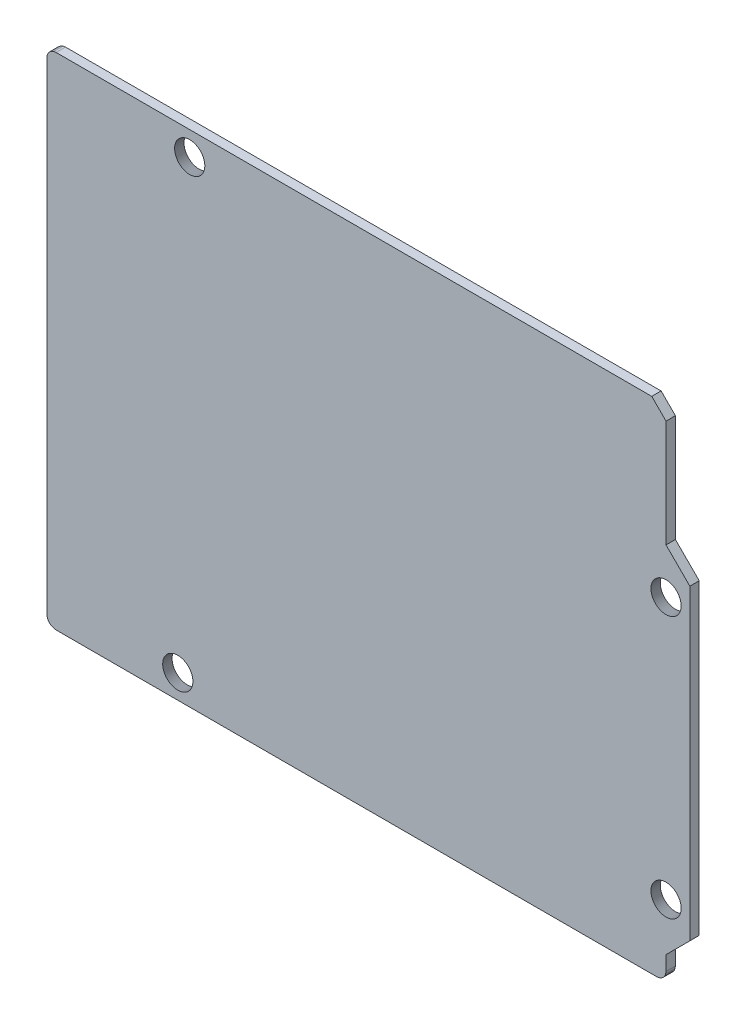
SolidWorks part; units mm, degrees
material "ПТФЭ (общий)"
ref_plane "Спереди" through (0, 0, 0) normal (0, 0, 1) x (1, 0, 0)
ref_plane "Сверху" through (0, 0, 0) normal (0, 1, 0) x (1, 0, 0)
ref_plane "Справа" through (0, 0, 0) normal (1, 0, 0) x (0, 0, -1)
sketch "Model" plane through (0, 0, 0) normal (0, 0, 1) x (1, 0, 0)
  line L0 (15.2346, 207.8414) -> (15.2907, 207.8424)
  line L1 (15.2907, 207.8424) -> (15.3468, 207.8453)
  line L2 (15.3468, 207.8453) -> (15.4027, 207.8502)
  line L3 (15.4027, 207.8502) -> (15.4584, 207.8571)
  line L4 (15.4584, 207.8571) -> (15.5139, 207.8658)
  line L5 (15.5139, 207.8658) -> (15.569, 207.8766)
  line L6 (15.569, 207.8766) -> (15.6237, 207.8892)
  line L7 (15.6237, 207.8892) -> (15.6779, 207.9037)
  line L8 (15.6779, 207.9037) -> (15.7315, 207.9201)
  line L9 (15.7315, 207.9201) -> (15.7846, 207.9384)
  line L10 (15.7846, 207.9384) -> (15.837, 207.9585)
  line L11 (15.837, 207.9585) -> (15.8887, 207.9804)
  line L12 (15.8887, 207.9804) -> (15.9396, 208.0042)
  line L13 (15.9396, 208.0042) -> (15.9896, 208.0296)
  line L14 (15.9896, 208.0296) -> (16.0387, 208.0569)
  line L15 (16.0387, 208.0569) -> (16.0868, 208.0858)
  line L16 (16.0868, 208.0858) -> (16.1339, 208.1163)
  line L17 (16.1339, 208.1163) -> (16.1798, 208.1485)
  line L18 (16.1798, 208.1485) -> (16.2247, 208.1823)
  line L19 (16.2247, 208.1823) -> (16.2683, 208.2176)
  line L20 (16.2683, 208.2176) -> (16.3106, 208.2545)
  line L21 (16.3106, 208.2545) -> (16.3517, 208.2927)
  line L22 (16.3517, 208.2927) -> (16.3914, 208.3324)
  line L23 (16.3914, 208.3324) -> (16.4297, 208.3735)
  line L24 (16.4297, 208.3735) -> (16.4665, 208.4158)
  line L25 (16.4665, 208.4158) -> (16.5018, 208.4595)
  line L26 (16.5018, 208.4595) -> (16.5356, 208.5043)
  line L27 (16.5356, 208.5043) -> (16.5678, 208.5503)
  line L28 (16.5678, 208.5503) -> (16.5984, 208.5974)
  line L29 (16.5984, 208.5974) -> (16.6273, 208.6455)
  line L30 (16.6273, 208.6455) -> (16.6545, 208.6946)
  line L31 (16.6545, 208.6946) -> (16.68, 208.7446)
  line L32 (16.68, 208.7446) -> (16.7037, 208.7954)
  line L33 (16.7037, 208.7954) -> (16.7256, 208.8471)
  line L34 (16.7256, 208.8471) -> (16.7457, 208.8995)
  line L35 (16.7457, 208.8995) -> (16.764, 208.9526)
  line L36 (16.764, 208.9526) -> (16.7804, 209.0063)
  line L37 (16.7804, 209.0063) -> (16.7949, 209.0605)
  line L38 (16.7949, 209.0605) -> (16.8076, 209.1152)
  line L39 (16.8076, 209.1152) -> (16.8183, 209.1703)
  line L40 (16.8183, 209.1703) -> (16.8271, 209.2257)
  line L41 (16.8271, 209.2257) -> (16.8339, 209.2814)
  line L42 (16.8339, 209.2814) -> (16.8388, 209.3373)
  line L43 (16.8388, 209.3373) -> (16.8417, 209.3934)
  line L44 (16.8417, 209.3934) -> (16.8427, 209.4495)
  line L45 (16.8427, 209.4495) -> (16.8418, 209.5052)
  line L46 (16.8418, 209.5052) -> (16.8389, 209.5609)
  line L47 (16.8389, 209.5609) -> (16.834, 209.6164)
  line L48 (16.834, 209.6164) -> (16.8273, 209.6717)
  line L49 (16.8273, 209.6717) -> (16.8186, 209.7267)
  line L50 (16.8186, 209.7267) -> (16.8081, 209.7814)
  line L51 (16.8081, 209.7814) -> (16.7956, 209.8357)
  line L52 (16.7956, 209.8357) -> (16.7813, 209.8896)
  line L53 (16.7813, 209.8896) -> (16.7652, 209.9429)
  line L54 (16.7652, 209.9429) -> (16.7471, 209.9956)
  line L55 (16.7471, 209.9956) -> (16.7273, 210.0477)
  line L56 (16.7273, 210.0477) -> (16.7057, 210.0991)
  line L57 (16.7057, 210.0991) -> (16.6823, 210.1496)
  line L58 (16.6823, 210.1496) -> (16.6572, 210.1994)
  line L59 (16.6572, 210.1994) -> (16.6304, 210.2482)
  line L60 (16.6304, 210.2482) -> (16.6018, 210.2961)
  line L61 (16.6018, 210.2961) -> (16.5717, 210.3429)
  line L62 (16.5717, 210.3429) -> (16.5399, 210.3887)
  line L63 (16.5399, 210.3887) -> (16.5066, 210.4334)
  line L64 (16.5066, 210.4334) -> (16.4718, 210.4768)
  line L65 (16.4718, 210.4768) -> (16.4354, 210.5191)
  line L66 (16.4354, 210.5191) -> (16.3977, 210.56)
  line L67 (16.3977, 210.56) -> (16.3585, 210.5997)
  line L68 (16.3585, 210.5997) -> (16.318, 210.6379)
  line L69 (16.318, 210.6379) -> (16.2762, 210.6747)
  line L70 (16.2762, 210.6747) -> (16.2331, 210.7101)
  line L71 (16.2331, 210.7101) -> (16.1888, 210.7439)
  line L72 (16.1888, 210.7439) -> (16.1434, 210.7762)
  line L73 (16.1434, 210.7762) -> (16.0969, 210.8069)
  line L74 (16.0969, 210.8069) -> (16.0494, 210.8359)
  line L75 (16.0494, 210.8359) -> (16.0008, 210.8633)
  line L76 (16.0008, 210.8633) -> (15.9514, 210.889)
  line L77 (15.9514, 210.889) -> (15.9011, 210.913)
  line L78 (15.9011, 210.913) -> (15.85, 210.9352)
  line L79 (15.85, 210.9352) -> (15.7982, 210.9556)
  line L80 (15.7982, 210.9556) -> (15.7457, 210.9742)
  line L81 (15.7457, 210.9742) -> (15.6925, 210.991)
  line L82 (15.6925, 210.991) -> (15.6389, 211.006)
  line L83 (15.6389, 211.006) -> (15.5847, 211.019)
  line L84 (15.5847, 211.019) -> (15.5301, 211.0302)
  line L85 (15.5301, 211.0302) -> (15.4752, 211.0395)
  line L86 (15.4752, 211.0395) -> (15.4199, 211.0469)
  line L87 (15.4199, 211.0469) -> (15.3645, 211.0524)
  line L88 (15.3645, 211.0524) -> (15.3089, 211.0559)
  line L89 (15.3089, 211.0559) -> (15.2532, 211.0575)
  line L90 (15.2532, 211.0575) -> (15.1975, 211.0572)
  line L91 (15.1975, 211.0572) -> (15.1418, 211.0549)
  line L92 (15.1418, 211.0549) -> (15.0862, 211.0508)
  line L93 (15.0862, 211.0508) -> (15.0309, 211.0447)
  line L94 (15.0309, 211.0447) -> (14.9757, 211.0366)
  line L95 (14.9757, 211.0366) -> (14.9209, 211.0267)
  line L96 (14.9209, 211.0267) -> (14.8664, 211.0149)
  line L97 (14.8664, 211.0149) -> (14.8124, 211.0012)
  line L98 (14.8124, 211.0012) -> (14.7589, 210.9856)
  line L99 (14.7589, 210.9856) -> (14.706, 210.9682)
  line L100 (14.706, 210.9682) -> (14.6537, 210.949)
  line L101 (14.6537, 210.949) -> (14.6021, 210.928)
  line L102 (14.6021, 210.928) -> (14.5513, 210.9052)
  line L103 (14.5513, 210.9052) -> (14.5012, 210.8806)
  line L104 (14.5012, 210.8806) -> (14.4521, 210.8544)
  line L105 (14.4521, 210.8544) -> (14.4039, 210.8264)
  line L106 (14.4039, 210.8264) -> (14.3567, 210.7968)
  line L107 (14.3567, 210.7968) -> (14.3106, 210.7656)
  line L108 (14.3106, 210.7656) -> (14.2655, 210.7328)
  line L109 (14.2655, 210.7328) -> (14.2216, 210.6985)
  line L110 (14.2216, 210.6985) -> (14.179, 210.6626)
  line L111 (14.179, 210.6626) -> (14.1376, 210.6253)
  line L112 (14.1376, 210.6253) -> (14.0975, 210.5866)
  line L113 (14.0975, 210.5866) -> (14.0588, 210.5465)
  line L114 (14.0588, 210.5465) -> (14.0215, 210.5051)
  line L115 (14.0215, 210.5051) -> (13.9857, 210.4625)
  line L116 (13.9857, 210.4625) -> (13.9513, 210.4186)
  line L117 (13.9513, 210.4186) -> (13.9185, 210.3736)
  line L118 (13.9185, 210.3736) -> (13.8873, 210.3274)
  line L119 (13.8873, 210.3274) -> (13.8577, 210.2802)
  line L120 (13.8577, 210.2802) -> (13.8297, 210.232)
  line L121 (13.8297, 210.232) -> (13.8035, 210.1829)
  line L122 (13.8035, 210.1829) -> (13.7789, 210.1329)
  line L123 (13.7789, 210.1329) -> (13.7561, 210.082)
  line L124 (13.7561, 210.082) -> (13.7351, 210.0304)
  line L125 (13.7351, 210.0304) -> (13.7159, 209.9781)
  line L126 (13.7159, 209.9781) -> (13.6985, 209.9252)
  line L127 (13.6985, 209.9252) -> (13.6829, 209.8717)
  line L128 (13.6829, 209.8717) -> (13.6692, 209.8177)
  line L129 (13.6692, 209.8177) -> (13.6574, 209.7632)
  line L130 (13.6574, 209.7632) -> (13.6475, 209.7084)
  line L131 (13.6475, 209.7084) -> (13.6395, 209.6533)
  line L132 (13.6395, 209.6533) -> (13.6334, 209.5979)
  line L133 (13.6334, 209.5979) -> (13.6292, 209.5423)
  line L134 (13.6292, 209.5423) -> (13.6269, 209.4867)
  line L135 (13.6269, 209.4867) -> (13.6266, 209.4309)
  line L136 (13.6266, 209.4309) -> (13.6282, 209.3752)
  line L137 (13.6282, 209.3752) -> (13.6318, 209.3196)
  line L138 (13.6318, 209.3196) -> (13.6372, 209.2642)
  line L139 (13.6372, 209.2642) -> (13.6446, 209.209)
  line L140 (13.6446, 209.209) -> (13.6539, 209.154)
  line L141 (13.6539, 209.154) -> (13.6651, 209.0994)
  line L142 (13.6651, 209.0994) -> (13.6782, 209.0453)
  line L143 (13.6782, 209.0453) -> (13.6931, 208.9916)
  line L144 (13.6931, 208.9916) -> (13.7099, 208.9385)
  line L145 (13.7099, 208.9385) -> (13.7285, 208.886)
  line L146 (13.7285, 208.886) -> (13.7489, 208.8341)
  line L147 (13.7489, 208.8341) -> (13.7711, 208.783)
  line L148 (13.7711, 208.783) -> (13.7951, 208.7327)
  line L149 (13.7951, 208.7327) -> (13.8208, 208.6833)
  line L150 (13.8208, 208.6833) -> (13.8482, 208.6348)
  line L151 (13.8482, 208.6348) -> (13.8773, 208.5872)
  line L152 (13.8773, 208.5872) -> (13.9079, 208.5407)
  line L153 (13.9079, 208.5407) -> (13.9402, 208.4953)
  line L154 (13.9402, 208.4953) -> (13.9741, 208.451)
  line L155 (13.9741, 208.451) -> (14.0094, 208.408)
  line L156 (14.0094, 208.408) -> (14.0462, 208.3661)
  line L157 (14.0462, 208.3661) -> (14.0845, 208.3256)
  line L158 (14.0845, 208.3256) -> (14.1241, 208.2865)
  line L159 (14.1241, 208.2865) -> (14.165, 208.2487)
  line L160 (14.165, 208.2487) -> (14.2073, 208.2123)
  line L161 (14.2073, 208.2123) -> (14.2508, 208.1775)
  line L162 (14.2508, 208.1775) -> (14.2954, 208.1442)
  line L163 (14.2954, 208.1442) -> (14.3412, 208.1124)
  line L164 (14.3412, 208.1124) -> (14.3881, 208.0823)
  line L165 (14.3881, 208.0823) -> (14.4359, 208.0538)
  line L166 (14.4359, 208.0538) -> (14.4848, 208.0269)
  line L167 (14.4848, 208.0269) -> (14.5345, 208.0018)
  line L168 (14.5345, 208.0018) -> (14.5851, 207.9784)
  line L169 (14.5851, 207.9784) -> (14.6364, 207.9568)
  line L170 (14.6364, 207.9568) -> (14.6885, 207.937)
  line L171 (14.6885, 207.937) -> (14.7412, 207.919)
  line L172 (14.7412, 207.919) -> (14.7945, 207.9028)
  line L173 (14.7945, 207.9028) -> (14.8484, 207.8885)
  line L174 (14.8484, 207.8885) -> (14.9027, 207.876)
  line L175 (14.9027, 207.876) -> (14.9574, 207.8655)
  line L176 (14.9574, 207.8655) -> (15.0124, 207.8568)
  line L177 (15.0124, 207.8568) -> (15.0678, 207.8501)
  line L178 (15.0678, 207.8501) -> (15.1233, 207.8453)
  line L179 (15.1233, 207.8453) -> (15.1789, 207.8424)
  line L180 (15.1789, 207.8424) -> (15.2346, 207.8414)
  line L1114 (0.9945, 211.9886) -> (64.4721, 211.9886)
  line L1115 (0.7406, 211.9463) -> (0.9945, 211.9886)
  line L1116 (0.5078, 211.8405) -> (0.7406, 211.9463)
  line L1117 (0.2962, 211.6924) -> (0.5078, 211.8405)
  line L1118 (0.127, 211.4808) -> (0.2962, 211.6924)
  line L1119 (0.0423, 211.248) -> (0.127, 211.4808)
  line L1120 (0, 210.973) -> (0.0423, 211.248)
  line L1121 (0, 159.6831) -> (0, 210.973)
  line L1122 (0.0423, 159.4292) -> (0, 159.6831)
  line L1123 (0.127, 159.1964) -> (0.0423, 159.4292)
  line L1124 (0.2962, 158.9848) -> (0.127, 159.1964)
  line L1125 (0.5078, 158.8156) -> (0.2962, 158.9848)
  line L1126 (0.7406, 158.7309) -> (0.5078, 158.8156)
  line L1127 (0.9945, 158.6886) -> (0.7406, 158.7309)
  line L1128 (65.001, 158.6886) -> (0.9945, 158.6886)
  line L1129 (65.2549, 158.7309) -> (65.001, 158.6886)
  line L1130 (65.4877, 158.8156) -> (65.2549, 158.7309)
  line L1131 (65.6993, 158.9848) -> (65.4877, 158.8156)
  line L1132 (65.8686, 159.1964) -> (65.6993, 158.9848)
  line L1133 (65.9532, 159.4292) -> (65.8686, 159.1964)
  line L1134 (65.9955, 159.6831) -> (65.9532, 159.4292)
  line L1135 (65.9955, 161.2277) -> (65.9955, 159.6831)
  line L1136 (68.5346, 163.7668) -> (65.9955, 161.2277)
  line L1137 (68.5346, 196.5001) -> (68.5346, 163.7668)
  line L1138 (65.9955, 199.0392) -> (68.5346, 196.5001)
  line L1139 (65.9955, 210.4652) -> (65.9955, 199.0392)
  line L1140 (64.4721, 211.9886) -> (65.9955, 210.4652)
  line L1141 (65.9955, 192.6068) -> (66.0516, 192.6078)
  line L1142 (66.0516, 192.6078) -> (66.1077, 192.6107)
  line L1143 (66.1077, 192.6107) -> (66.1636, 192.6156)
  line L1144 (66.1636, 192.6156) -> (66.2193, 192.6224)
  line L1145 (66.2193, 192.6224) -> (66.2748, 192.6312)
  line L1146 (66.2748, 192.6312) -> (66.3299, 192.6419)
  line L1147 (66.3299, 192.6419) -> (66.3845, 192.6546)
  line L1148 (66.3845, 192.6546) -> (66.4388, 192.6691)
  line L1149 (66.4388, 192.6691) -> (66.4924, 192.6855)
  line L1150 (66.4924, 192.6855) -> (66.5455, 192.7038)
  line L1151 (66.5455, 192.7038) -> (66.5979, 192.7239)
  line L1152 (66.5979, 192.7239) -> (66.6496, 192.7458)
  line L1153 (66.6496, 192.7458) -> (66.7005, 192.7695)
  line L1154 (66.7005, 192.7695) -> (66.7505, 192.795)
  line L1155 (66.7505, 192.795) -> (66.7996, 192.8222)
  line L1156 (66.7996, 192.8222) -> (66.8477, 192.8512)
  line L1157 (66.8477, 192.8512) -> (66.8948, 192.8817)
  line L1158 (66.8948, 192.8817) -> (66.9407, 192.9139)
  line L1159 (66.9407, 192.9139) -> (66.9856, 192.9477)
  line L1160 (66.9856, 192.9477) -> (67.0292, 192.983)
  line L1161 (67.0292, 192.983) -> (67.0715, 193.0198)
  line L1162 (67.0715, 193.0198) -> (67.1126, 193.0581)
  line L1163 (67.1126, 193.0581) -> (67.1523, 193.0978)
  line L1164 (67.1523, 193.0978) -> (67.1906, 193.1389)
  line L1165 (67.1906, 193.1389) -> (67.2274, 193.1812)
  line L1166 (67.2274, 193.1812) -> (67.2627, 193.2249)
  line L1167 (67.2627, 193.2249) -> (67.2965, 193.2697)
  line L1168 (67.2965, 193.2697) -> (67.3287, 193.3157)
  line L1169 (67.3287, 193.3157) -> (67.3593, 193.3627)
  line L1170 (67.3593, 193.3627) -> (67.3882, 193.4108)
  line L1171 (67.3882, 193.4108) -> (67.4154, 193.4599)
  line L1172 (67.4154, 193.4599) -> (67.4409, 193.51)
  line L1173 (67.4409, 193.51) -> (67.4646, 193.5608)
  line L1174 (67.4646, 193.5608) -> (67.4865, 193.6125)
  line L1175 (67.4865, 193.6125) -> (67.5066, 193.6649)
  line L1176 (67.5066, 193.6649) -> (67.5249, 193.718)
  line L1177 (67.5249, 193.718) -> (67.5413, 193.7716)
  line L1178 (67.5413, 193.7716) -> (67.5558, 193.8259)
  line L1179 (67.5558, 193.8259) -> (67.5685, 193.8806)
  line L1180 (67.5685, 193.8806) -> (67.5792, 193.9357)
  line L1181 (67.5792, 193.9357) -> (67.588, 193.9911)
  line L1182 (67.588, 193.9911) -> (67.5948, 194.0468)
  line L1183 (67.5948, 194.0468) -> (67.5997, 194.1027)
  line L1184 (67.5997, 194.1027) -> (67.6026, 194.1588)
  line L1185 (67.6026, 194.1588) -> (67.6036, 194.2149)
  line L1186 (67.6036, 194.2149) -> (67.6026, 194.2706)
  line L1187 (67.6026, 194.2706) -> (67.5998, 194.3262)
  line L1188 (67.5998, 194.3262) -> (67.5949, 194.3818)
  line L1189 (67.5949, 194.3818) -> (67.5882, 194.4371)
  line L1190 (67.5882, 194.4371) -> (67.5795, 194.4921)
  line L1191 (67.5795, 194.4921) -> (67.569, 194.5468)
  line L1192 (67.569, 194.5468) -> (67.5565, 194.6011)
  line L1193 (67.5565, 194.6011) -> (67.5422, 194.655)
  line L1194 (67.5422, 194.655) -> (67.5261, 194.7083)
  line L1195 (67.5261, 194.7083) -> (67.508, 194.761)
  line L1196 (67.508, 194.761) -> (67.4882, 194.8131)
  line L1197 (67.4882, 194.8131) -> (67.4666, 194.8644)
  line L1198 (67.4666, 194.8644) -> (67.4432, 194.915)
  line L1199 (67.4432, 194.915) -> (67.4181, 194.9647)
  line L1200 (67.4181, 194.9647) -> (67.3913, 195.0136)
  line L1201 (67.3913, 195.0136) -> (67.3627, 195.0615)
  line L1202 (67.3627, 195.0615) -> (67.3326, 195.1083)
  line L1203 (67.3326, 195.1083) -> (67.3008, 195.1541)
  line L1204 (67.3008, 195.1541) -> (67.2675, 195.1987)
  line L1205 (67.2675, 195.1987) -> (67.2327, 195.2422)
  line L1206 (67.2327, 195.2422) -> (67.1963, 195.2845)
  line L1207 (67.1963, 195.2845) -> (67.1586, 195.3254)
  line L1208 (67.1586, 195.3254) -> (67.1194, 195.3651)
  line L1209 (67.1194, 195.3651) -> (67.0789, 195.4033)
  line L1210 (67.0789, 195.4033) -> (67.0371, 195.4401)
  line L1211 (67.0371, 195.4401) -> (66.994, 195.4755)
  line L1212 (66.994, 195.4755) -> (66.9497, 195.5093)
  line L1213 (66.9497, 195.5093) -> (66.9043, 195.5416)
  line L1214 (66.9043, 195.5416) -> (66.8578, 195.5723)
  line L1215 (66.8578, 195.5723) -> (66.8103, 195.6013)
  line L1216 (66.8103, 195.6013) -> (66.7617, 195.6287)
  line L1217 (66.7617, 195.6287) -> (66.7123, 195.6544)
  line L1218 (66.7123, 195.6544) -> (66.662, 195.6784)
  line L1219 (66.662, 195.6784) -> (66.6109, 195.7006)
  line L1220 (66.6109, 195.7006) -> (66.5591, 195.721)
  line L1221 (66.5591, 195.721) -> (66.5066, 195.7396)
  line L1222 (66.5066, 195.7396) -> (66.4534, 195.7564)
  line L1223 (66.4534, 195.7564) -> (66.3997, 195.7714)
  line L1224 (66.3997, 195.7714) -> (66.3456, 195.7844)
  line L1225 (66.3456, 195.7844) -> (66.291, 195.7956)
  line L1226 (66.291, 195.7956) -> (66.2361, 195.8049)
  line L1227 (66.2361, 195.8049) -> (66.1808, 195.8123)
  line L1228 (66.1808, 195.8123) -> (66.1254, 195.8177)
  line L1229 (66.1254, 195.8177) -> (66.0698, 195.8213)
  line L1230 (66.0698, 195.8213) -> (66.0141, 195.8229)
  line L1231 (66.0141, 195.8229) -> (65.9584, 195.8226)
  line L1232 (65.9584, 195.8226) -> (65.9027, 195.8203)
  line L1233 (65.9027, 195.8203) -> (65.8471, 195.8161)
  line L1234 (65.8471, 195.8161) -> (65.7918, 195.81)
  line L1235 (65.7918, 195.81) -> (65.7366, 195.802)
  line L1236 (65.7366, 195.802) -> (65.6818, 195.7921)
  line L1237 (65.6818, 195.7921) -> (65.6273, 195.7803)
  line L1238 (65.6273, 195.7803) -> (65.5733, 195.7666)
  line L1239 (65.5733, 195.7666) -> (65.5198, 195.751)
  line L1240 (65.5198, 195.751) -> (65.4669, 195.7336)
  line L1241 (65.4669, 195.7336) -> (65.4146, 195.7144)
  line L1242 (65.4146, 195.7144) -> (65.363, 195.6934)
  line L1243 (65.363, 195.6934) -> (65.3122, 195.6706)
  line L1244 (65.3122, 195.6706) -> (65.2621, 195.646)
  line L1245 (65.2621, 195.646) -> (65.213, 195.6198)
  line L1246 (65.213, 195.6198) -> (65.1648, 195.5918)
  line L1247 (65.1648, 195.5918) -> (65.1176, 195.5622)
  line L1248 (65.1176, 195.5622) -> (65.0715, 195.531)
  line L1249 (65.0715, 195.531) -> (65.0264, 195.4982)
  line L1250 (65.0264, 195.4982) -> (64.9825, 195.4638)
  line L1251 (64.9825, 195.4638) -> (64.9399, 195.428)
  line L1252 (64.9399, 195.428) -> (64.8985, 195.3907)
  line L1253 (64.8985, 195.3907) -> (64.8584, 195.352)
  line L1254 (64.8584, 195.352) -> (64.8197, 195.3119)
  line L1255 (64.8197, 195.3119) -> (64.7824, 195.2705)
  line L1256 (64.7824, 195.2705) -> (64.7466, 195.2279)
  line L1257 (64.7466, 195.2279) -> (64.7122, 195.184)
  line L1258 (64.7122, 195.184) -> (64.6794, 195.139)
  line L1259 (64.6794, 195.139) -> (64.6482, 195.0928)
  line L1260 (64.6482, 195.0928) -> (64.6186, 195.0456)
  line L1261 (64.6186, 195.0456) -> (64.5906, 194.9974)
  line L1262 (64.5906, 194.9974) -> (64.5644, 194.9483)
  line L1263 (64.5644, 194.9483) -> (64.5398, 194.8982)
  line L1264 (64.5398, 194.8982) -> (64.517, 194.8474)
  line L1265 (64.517, 194.8474) -> (64.496, 194.7958)
  line L1266 (64.496, 194.7958) -> (64.4768, 194.7435)
  line L1267 (64.4768, 194.7435) -> (64.4594, 194.6906)
  line L1268 (64.4594, 194.6906) -> (64.4438, 194.6371)
  line L1269 (64.4438, 194.6371) -> (64.4301, 194.5831)
  line L1270 (64.4301, 194.5831) -> (64.4183, 194.5286)
  line L1271 (64.4183, 194.5286) -> (64.4084, 194.4738)
  line L1272 (64.4084, 194.4738) -> (64.4004, 194.4187)
  line L1273 (64.4004, 194.4187) -> (64.3943, 194.3633)
  line L1274 (64.3943, 194.3633) -> (64.3901, 194.3077)
  line L1275 (64.3901, 194.3077) -> (64.3878, 194.252)
  line L1276 (64.3878, 194.252) -> (64.3875, 194.1963)
  line L1277 (64.3875, 194.1963) -> (64.3891, 194.1406)
  line L1278 (64.3891, 194.1406) -> (64.3927, 194.085)
  line L1279 (64.3927, 194.085) -> (64.3981, 194.0296)
  line L1280 (64.3981, 194.0296) -> (64.4055, 193.9743)
  line L1281 (64.4055, 193.9743) -> (64.4148, 193.9194)
  line L1282 (64.4148, 193.9194) -> (64.426, 193.8648)
  line L1283 (64.426, 193.8648) -> (64.4391, 193.8107)
  line L1284 (64.4391, 193.8107) -> (64.454, 193.757)
  line L1285 (64.454, 193.757) -> (64.4708, 193.7039)
  line L1286 (64.4708, 193.7039) -> (64.4894, 193.6513)
  line L1287 (64.4894, 193.6513) -> (64.5098, 193.5995)
  line L1288 (64.5098, 193.5995) -> (64.532, 193.5484)
  line L1289 (64.532, 193.5484) -> (64.556, 193.4981)
  line L1290 (64.556, 193.4981) -> (64.5817, 193.4487)
  line L1291 (64.5817, 193.4487) -> (64.6091, 193.4001)
  line L1292 (64.6091, 193.4001) -> (64.6381, 193.3526)
  line L1293 (64.6381, 193.3526) -> (64.6688, 193.3061)
  line L1294 (64.6688, 193.3061) -> (64.7011, 193.2607)
  line L1295 (64.7011, 193.2607) -> (64.735, 193.2164)
  line L1296 (64.735, 193.2164) -> (64.7703, 193.1733)
  line L1297 (64.7703, 193.1733) -> (64.8071, 193.1315)
  line L1298 (64.8071, 193.1315) -> (64.8454, 193.091)
  line L1299 (64.8454, 193.091) -> (64.885, 193.0518)
  line L1300 (64.885, 193.0518) -> (64.9259, 193.0141)
  line L1301 (64.9259, 193.0141) -> (64.9682, 192.9777)
  line L1302 (64.9682, 192.9777) -> (65.0117, 192.9429)
  line L1303 (65.0117, 192.9429) -> (65.0563, 192.9096)
  line L1304 (65.0563, 192.9096) -> (65.1021, 192.8778)
  line L1305 (65.1021, 192.8778) -> (65.149, 192.8477)
  line L1306 (65.149, 192.8477) -> (65.1968, 192.8192)
  line L1307 (65.1968, 192.8192) -> (65.2457, 192.7923)
  line L1308 (65.2457, 192.7923) -> (65.2954, 192.7672)
  line L1309 (65.2954, 192.7672) -> (65.346, 192.7438)
  line L1310 (65.346, 192.7438) -> (65.3973, 192.7222)
  line L1311 (65.3973, 192.7222) -> (65.4494, 192.7024)
  line L1312 (65.4494, 192.7024) -> (65.5021, 192.6844)
  line L1313 (65.5021, 192.6844) -> (65.5554, 192.6682)
  line L1314 (65.5554, 192.6682) -> (65.6093, 192.6539)
  line L1315 (65.6093, 192.6539) -> (65.6636, 192.6414)
  line L1316 (65.6636, 192.6414) -> (65.7183, 192.6309)
  line L1317 (65.7183, 192.6309) -> (65.7733, 192.6222)
  line L1318 (65.7733, 192.6222) -> (65.8287, 192.6155)
  line L1319 (65.8287, 192.6155) -> (65.8842, 192.6107)
  line L1320 (65.8842, 192.6107) -> (65.9398, 192.6078)
  line L1321 (65.9398, 192.6078) -> (65.9955, 192.6068)
  line L1322 (13.9651, 159.6196) -> (14.0212, 159.6206)
  line L1323 (14.0212, 159.6206) -> (14.0772, 159.6235)
  line L1324 (14.0772, 159.6235) -> (14.1332, 159.6284)
  line L1325 (14.1332, 159.6284) -> (14.1889, 159.6353)
  line L1326 (14.1889, 159.6353) -> (14.2443, 159.6441)
  line L1327 (14.2443, 159.6441) -> (14.2994, 159.6548)
  line L1328 (14.2994, 159.6548) -> (14.3541, 159.6674)
  line L1329 (14.3541, 159.6674) -> (14.4083, 159.6819)
  line L1330 (14.4083, 159.6819) -> (14.462, 159.6983)
  line L1331 (14.462, 159.6983) -> (14.5151, 159.7166)
  line L1332 (14.5151, 159.7166) -> (14.5675, 159.7367)
  line L1333 (14.5675, 159.7367) -> (14.6191, 159.7586)
  line L1334 (14.6191, 159.7586) -> (14.67, 159.7824)
  line L1335 (14.67, 159.7824) -> (14.72, 159.8079)
  line L1336 (14.72, 159.8079) -> (14.7691, 159.8351)
  line L1337 (14.7691, 159.8351) -> (14.8172, 159.864)
  line L1338 (14.8172, 159.864) -> (14.8643, 159.8945)
  line L1339 (14.8643, 159.8945) -> (14.9103, 159.9267)
  line L1340 (14.9103, 159.9267) -> (14.9551, 159.9605)
  line L1341 (14.9551, 159.9605) -> (14.9987, 159.9958)
  line L1342 (14.9987, 159.9958) -> (15.0411, 160.0327)
  line L1343 (15.0411, 160.0327) -> (15.0821, 160.0709)
  line L1344 (15.0821, 160.0709) -> (15.1218, 160.1106)
  line L1345 (15.1218, 160.1106) -> (15.1601, 160.1517)
  line L1346 (15.1601, 160.1517) -> (15.1969, 160.1941)
  line L1347 (15.1969, 160.1941) -> (15.2323, 160.2377)
  line L1348 (15.2323, 160.2377) -> (15.266, 160.2825)
  line L1349 (15.266, 160.2825) -> (15.2982, 160.3285)
  line L1350 (15.2982, 160.3285) -> (15.3288, 160.3756)
  line L1351 (15.3288, 160.3756) -> (15.3577, 160.4237)
  line L1352 (15.3577, 160.4237) -> (15.3849, 160.4728)
  line L1353 (15.3849, 160.4728) -> (15.4104, 160.5228)
  line L1354 (15.4104, 160.5228) -> (15.4341, 160.5736)
  line L1355 (15.4341, 160.5736) -> (15.4561, 160.6253)
  line L1356 (15.4561, 160.6253) -> (15.4762, 160.6777)
  line L1357 (15.4762, 160.6777) -> (15.4945, 160.7308)
  line L1358 (15.4945, 160.7308) -> (15.5109, 160.7845)
  line L1359 (15.5109, 160.7845) -> (15.5254, 160.8387)
  line L1360 (15.5254, 160.8387) -> (15.538, 160.8934)
  line L1361 (15.538, 160.8934) -> (15.5487, 160.9485)
  line L1362 (15.5487, 160.9485) -> (15.5575, 161.0039)
  line L1363 (15.5575, 161.0039) -> (15.5644, 161.0596)
  line L1364 (15.5644, 161.0596) -> (15.5692, 161.1155)
  line L1365 (15.5692, 161.1155) -> (15.5722, 161.1716)
  line L1366 (15.5722, 161.1716) -> (15.5732, 161.2277)
  line L1367 (15.5732, 161.2277) -> (15.5722, 161.2834)
  line L1368 (15.5722, 161.2834) -> (15.5693, 161.3391)
  line L1369 (15.5693, 161.3391) -> (15.5645, 161.3946)
  line L1370 (15.5645, 161.3946) -> (15.5577, 161.4499)
  line L1371 (15.5577, 161.4499) -> (15.5491, 161.5049)
  line L1372 (15.5491, 161.5049) -> (15.5385, 161.5596)
  line L1373 (15.5385, 161.5596) -> (15.5261, 161.6139)
  line L1374 (15.5261, 161.6139) -> (15.5118, 161.6678)
  line L1375 (15.5118, 161.6678) -> (15.4956, 161.7211)
  line L1376 (15.4956, 161.7211) -> (15.4776, 161.7738)
  line L1377 (15.4776, 161.7738) -> (15.4578, 161.8259)
  line L1378 (15.4578, 161.8259) -> (15.4361, 161.8773)
  line L1379 (15.4361, 161.8773) -> (15.4128, 161.9278)
  line L1380 (15.4128, 161.9278) -> (15.3876, 161.9776)
  line L1381 (15.3876, 161.9776) -> (15.3608, 162.0264)
  line L1382 (15.3608, 162.0264) -> (15.3323, 162.0743)
  line L1383 (15.3323, 162.0743) -> (15.3022, 162.1211)
  line L1384 (15.3022, 162.1211) -> (15.2704, 162.1669)
  line L1385 (15.2704, 162.1669) -> (15.2371, 162.2116)
  line L1386 (15.2371, 162.2116) -> (15.2022, 162.255)
  line L1387 (15.2022, 162.255) -> (15.1659, 162.2973)
  line L1388 (15.1659, 162.2973) -> (15.1281, 162.3382)
  line L1389 (15.1281, 162.3382) -> (15.089, 162.3779)
  line L1390 (15.089, 162.3779) -> (15.0484, 162.4161)
  line L1391 (15.0484, 162.4161) -> (15.0066, 162.4529)
  line L1392 (15.0066, 162.4529) -> (14.9635, 162.4883)
  line L1393 (14.9635, 162.4883) -> (14.9193, 162.5221)
  line L1394 (14.9193, 162.5221) -> (14.8739, 162.5544)
  line L1395 (14.8739, 162.5544) -> (14.8274, 162.5851)
  line L1396 (14.8274, 162.5851) -> (14.7798, 162.6141)
  line L1397 (14.7798, 162.6141) -> (14.7313, 162.6415)
  line L1398 (14.7313, 162.6415) -> (14.6819, 162.6672)
  line L1399 (14.6819, 162.6672) -> (14.6316, 162.6912)
  line L1400 (14.6316, 162.6912) -> (14.5805, 162.7134)
  line L1401 (14.5805, 162.7134) -> (14.5286, 162.7338)
  line L1402 (14.5286, 162.7338) -> (14.4761, 162.7525)
  line L1403 (14.4761, 162.7525) -> (14.423, 162.7692)
  line L1404 (14.423, 162.7692) -> (14.3693, 162.7842)
  line L1405 (14.3693, 162.7842) -> (14.3151, 162.7973)
  line L1406 (14.3151, 162.7973) -> (14.2606, 162.8084)
  line L1407 (14.2606, 162.8084) -> (14.2056, 162.8177)
  line L1408 (14.2056, 162.8177) -> (14.1504, 162.8251)
  line L1409 (14.1504, 162.8251) -> (14.0949, 162.8306)
  line L1410 (14.0949, 162.8306) -> (14.0393, 162.8341)
  line L1411 (14.0393, 162.8341) -> (13.9836, 162.8357)
  line L1412 (13.9836, 162.8357) -> (13.9279, 162.8354)
  line L1413 (13.9279, 162.8354) -> (13.8722, 162.8331)
  line L1414 (13.8722, 162.8331) -> (13.8167, 162.829)
  line L1415 (13.8167, 162.829) -> (13.7613, 162.8229)
  line L1416 (13.7613, 162.8229) -> (13.7062, 162.8148)
  line L1417 (13.7062, 162.8148) -> (13.6513, 162.8049)
  line L1418 (13.6513, 162.8049) -> (13.5969, 162.7931)
  line L1419 (13.5969, 162.7931) -> (13.5429, 162.7794)
  line L1420 (13.5429, 162.7794) -> (13.4894, 162.7639)
  line L1421 (13.4894, 162.7639) -> (13.4364, 162.7465)
  line L1422 (13.4364, 162.7465) -> (13.3842, 162.7272)
  line L1423 (13.3842, 162.7272) -> (13.3326, 162.7062)
  line L1424 (13.3326, 162.7062) -> (13.2817, 162.6834)
  line L1425 (13.2817, 162.6834) -> (13.2317, 162.6589)
  line L1426 (13.2317, 162.6589) -> (13.1826, 162.6326)
  line L1427 (13.1826, 162.6326) -> (13.1344, 162.6046)
  line L1428 (13.1344, 162.6046) -> (13.0872, 162.575)
  line L1429 (13.0872, 162.575) -> (13.041, 162.5438)
  line L1430 (13.041, 162.5438) -> (12.996, 162.511)
  line L1431 (12.996, 162.511) -> (12.9521, 162.4767)
  line L1432 (12.9521, 162.4767) -> (12.9094, 162.4408)
  line L1433 (12.9094, 162.4408) -> (12.868, 162.4035)
  line L1434 (12.868, 162.4035) -> (12.828, 162.3648)
  line L1435 (12.828, 162.3648) -> (12.7893, 162.3247)
  line L1436 (12.7893, 162.3247) -> (12.752, 162.2833)
  line L1437 (12.752, 162.2833) -> (12.7161, 162.2407)
  line L1438 (12.7161, 162.2407) -> (12.6818, 162.1968)
  line L1439 (12.6818, 162.1968) -> (12.649, 162.1518)
  line L1440 (12.649, 162.1518) -> (12.6178, 162.1056)
  line L1441 (12.6178, 162.1056) -> (12.5881, 162.0584)
  line L1442 (12.5881, 162.0584) -> (12.5602, 162.0102)
  line L1443 (12.5602, 162.0102) -> (12.5339, 161.9611)
  line L1444 (12.5339, 161.9611) -> (12.5094, 161.9111)
  line L1445 (12.5094, 161.9111) -> (12.4866, 161.8602)
  line L1446 (12.4866, 161.8602) -> (12.4656, 161.8086)
  line L1447 (12.4656, 161.8086) -> (12.4463, 161.7563)
  line L1448 (12.4463, 161.7563) -> (12.4289, 161.7034)
  line L1449 (12.4289, 161.7034) -> (12.4134, 161.6499)
  line L1450 (12.4134, 161.6499) -> (12.3997, 161.5959)
  line L1451 (12.3997, 161.5959) -> (12.3879, 161.5414)
  line L1452 (12.3879, 161.5414) -> (12.3779, 161.4866)
  line L1453 (12.3779, 161.4866) -> (12.3699, 161.4315)
  line L1454 (12.3699, 161.4315) -> (12.3638, 161.3761)
  line L1455 (12.3638, 161.3761) -> (12.3596, 161.3205)
  line L1456 (12.3596, 161.3205) -> (12.3574, 161.2649)
  line L1457 (12.3574, 161.2649) -> (12.3571, 161.2091)
  line L1458 (12.3571, 161.2091) -> (12.3587, 161.1535)
  line L1459 (12.3587, 161.1535) -> (12.3622, 161.0978)
  line L1460 (12.3622, 161.0978) -> (12.3677, 161.0424)
  line L1461 (12.3677, 161.0424) -> (12.3751, 160.9872)
  line L1462 (12.3751, 160.9872) -> (12.3843, 160.9322)
  line L1463 (12.3843, 160.9322) -> (12.3955, 160.8776)
  line L1464 (12.3955, 160.8776) -> (12.4086, 160.8235)
  line L1465 (12.4086, 160.8235) -> (12.4235, 160.7698)
  line L1466 (12.4235, 160.7698) -> (12.4403, 160.7167)
  line L1467 (12.4403, 160.7167) -> (12.4589, 160.6642)
  line L1468 (12.4589, 160.6642) -> (12.4794, 160.6123)
  line L1469 (12.4794, 160.6123) -> (12.5016, 160.5612)
  line L1470 (12.5016, 160.5612) -> (12.5256, 160.5109)
  line L1471 (12.5256, 160.5109) -> (12.5513, 160.4615)
  line L1472 (12.5513, 160.4615) -> (12.5786, 160.413)
  line L1473 (12.5786, 160.413) -> (12.6077, 160.3654)
  line L1474 (12.6077, 160.3654) -> (12.6384, 160.3189)
  line L1475 (12.6384, 160.3189) -> (12.6707, 160.2735)
  line L1476 (12.6707, 160.2735) -> (12.7045, 160.2292)
  line L1477 (12.7045, 160.2292) -> (12.7398, 160.1862)
  line L1478 (12.7398, 160.1862) -> (12.7767, 160.1444)
  line L1479 (12.7767, 160.1444) -> (12.8149, 160.1038)
  line L1480 (12.8149, 160.1038) -> (12.8545, 160.0647)
  line L1481 (12.8545, 160.0647) -> (12.8955, 160.0269)
  line L1482 (12.8955, 160.0269) -> (12.9377, 159.9906)
  line L1483 (12.9377, 159.9906) -> (12.9812, 159.9557)
  line L1484 (12.9812, 159.9557) -> (13.0259, 159.9224)
  line L1485 (13.0259, 159.9224) -> (13.0717, 159.8906)
  line L1486 (13.0717, 159.8906) -> (13.1185, 159.8605)
  line L1487 (13.1185, 159.8605) -> (13.1664, 159.832)
  line L1488 (13.1664, 159.832) -> (13.2152, 159.8051)
  line L1489 (13.2152, 159.8051) -> (13.2649, 159.78)
  line L1490 (13.2649, 159.78) -> (13.3155, 159.7566)
  line L1491 (13.3155, 159.7566) -> (13.3669, 159.735)
  line L1492 (13.3669, 159.735) -> (13.4189, 159.7152)
  line L1493 (13.4189, 159.7152) -> (13.4717, 159.6972)
  line L1494 (13.4717, 159.6972) -> (13.525, 159.681)
  line L1495 (13.525, 159.681) -> (13.5788, 159.6667)
  line L1496 (13.5788, 159.6667) -> (13.6331, 159.6542)
  line L1497 (13.6331, 159.6542) -> (13.6879, 159.6437)
  line L1498 (13.6879, 159.6437) -> (13.7429, 159.635)
  line L1499 (13.7429, 159.635) -> (13.7982, 159.6283)
  line L1500 (13.7982, 159.6283) -> (13.8537, 159.6235)
  line L1501 (13.8537, 159.6235) -> (13.9094, 159.6206)
  line L1502 (13.9094, 159.6206) -> (13.9651, 159.6196)
  line L1503 (65.9955, 164.6978) -> (66.0516, 164.6988)
  line L1504 (66.0516, 164.6988) -> (66.1077, 164.7017)
  line L1505 (66.1077, 164.7017) -> (66.1636, 164.7066)
  line L1506 (66.1636, 164.7066) -> (66.2193, 164.7135)
  line L1507 (66.2193, 164.7135) -> (66.2748, 164.7223)
  line L1508 (66.2748, 164.7223) -> (66.3299, 164.733)
  line L1509 (66.3299, 164.733) -> (66.3845, 164.7456)
  line L1510 (66.3845, 164.7456) -> (66.4388, 164.7601)
  line L1511 (66.4388, 164.7601) -> (66.4924, 164.7765)
  line L1512 (66.4924, 164.7765) -> (66.5455, 164.7948)
  line L1513 (66.5455, 164.7948) -> (66.5979, 164.8149)
  line L1514 (66.5979, 164.8149) -> (66.6496, 164.8369)
  line L1515 (66.6496, 164.8369) -> (66.7005, 164.8606)
  line L1516 (66.7005, 164.8606) -> (66.7505, 164.8861)
  line L1517 (66.7505, 164.8861) -> (66.7996, 164.9133)
  line L1518 (66.7996, 164.9133) -> (66.8477, 164.9422)
  line L1519 (66.8477, 164.9422) -> (66.8948, 164.9728)
  line L1520 (66.8948, 164.9728) -> (66.9407, 165.0049)
  line L1521 (66.9407, 165.0049) -> (66.9856, 165.0387)
  line L1522 (66.9856, 165.0387) -> (67.0292, 165.074)
  line L1523 (67.0292, 165.074) -> (67.0715, 165.1109)
  line L1524 (67.0715, 165.1109) -> (67.1126, 165.1492)
  line L1525 (67.1126, 165.1492) -> (67.1523, 165.1888)
  line L1526 (67.1523, 165.1888) -> (67.1906, 165.2299)
  line L1527 (67.1906, 165.2299) -> (67.2274, 165.2723)
  line L1528 (67.2274, 165.2723) -> (67.2627, 165.3159)
  line L1529 (67.2627, 165.3159) -> (67.2965, 165.3607)
  line L1530 (67.2965, 165.3607) -> (67.3287, 165.4067)
  line L1531 (67.3287, 165.4067) -> (67.3593, 165.4538)
  line L1532 (67.3593, 165.4538) -> (67.3882, 165.5019)
  line L1533 (67.3882, 165.5019) -> (67.4154, 165.551)
  line L1534 (67.4154, 165.551) -> (67.4409, 165.601)
  line L1535 (67.4409, 165.601) -> (67.4646, 165.6519)
  line L1536 (67.4646, 165.6519) -> (67.4865, 165.7035)
  line L1537 (67.4865, 165.7035) -> (67.5066, 165.7559)
  line L1538 (67.5066, 165.7559) -> (67.5249, 165.809)
  line L1539 (67.5249, 165.809) -> (67.5413, 165.8627)
  line L1540 (67.5413, 165.8627) -> (67.5558, 165.9169)
  line L1541 (67.5558, 165.9169) -> (67.5685, 165.9716)
  line L1542 (67.5685, 165.9716) -> (67.5792, 166.0267)
  line L1543 (67.5792, 166.0267) -> (67.588, 166.0821)
  line L1544 (67.588, 166.0821) -> (67.5948, 166.1378)
  line L1545 (67.5948, 166.1378) -> (67.5997, 166.1937)
  line L1546 (67.5997, 166.1937) -> (67.6026, 166.2498)
  line L1547 (67.6026, 166.2498) -> (67.6036, 166.3059)
  line L1548 (67.6036, 166.3059) -> (67.6026, 166.3616)
  line L1549 (67.6026, 166.3616) -> (67.5998, 166.4173)
  line L1550 (67.5998, 166.4173) -> (67.5949, 166.4728)
  line L1551 (67.5949, 166.4728) -> (67.5882, 166.5281)
  line L1552 (67.5882, 166.5281) -> (67.5795, 166.5831)
  line L1553 (67.5795, 166.5831) -> (67.569, 166.6378)
  line L1554 (67.569, 166.6378) -> (67.5565, 166.6922)
  line L1555 (67.5565, 166.6922) -> (67.5422, 166.746)
  line L1556 (67.5422, 166.746) -> (67.5261, 166.7993)
  line L1557 (67.5261, 166.7993) -> (67.508, 166.852)
  line L1558 (67.508, 166.852) -> (67.4882, 166.9041)
  line L1559 (67.4882, 166.9041) -> (67.4666, 166.9555)
  line L1560 (67.4666, 166.9555) -> (67.4432, 167.006)
  line L1561 (67.4432, 167.006) -> (67.4181, 167.0558)
  line L1562 (67.4181, 167.0558) -> (67.3913, 167.1046)
  line L1563 (67.3913, 167.1046) -> (67.3627, 167.1525)
  line L1564 (67.3627, 167.1525) -> (67.3326, 167.1993)
  line L1565 (67.3326, 167.1993) -> (67.3008, 167.2451)
  line L1566 (67.3008, 167.2451) -> (67.2675, 167.2898)
  line L1567 (67.2675, 167.2898) -> (67.2327, 167.3333)
  line L1568 (67.2327, 167.3333) -> (67.1963, 167.3755)
  line L1569 (67.1963, 167.3755) -> (67.1586, 167.4165)
  line L1570 (67.1586, 167.4165) -> (67.1194, 167.4561)
  line L1571 (67.1194, 167.4561) -> (67.0789, 167.4943)
  line L1572 (67.0789, 167.4943) -> (67.0371, 167.5311)
  line L1573 (67.0371, 167.5311) -> (66.994, 167.5665)
  line L1574 (66.994, 167.5665) -> (66.9497, 167.6003)
  line L1575 (66.9497, 167.6003) -> (66.9043, 167.6326)
  line L1576 (66.9043, 167.6326) -> (66.8578, 167.6633)
  line L1577 (66.8578, 167.6633) -> (66.8103, 167.6923)
  line L1578 (66.8103, 167.6923) -> (66.7617, 167.7197)
  line L1579 (66.7617, 167.7197) -> (66.7123, 167.7454)
  line L1580 (66.7123, 167.7454) -> (66.662, 167.7694)
  line L1581 (66.662, 167.7694) -> (66.6109, 167.7916)
  line L1582 (66.6109, 167.7916) -> (66.5591, 167.812)
  line L1583 (66.5591, 167.812) -> (66.5066, 167.8307)
  line L1584 (66.5066, 167.8307) -> (66.4534, 167.8474)
  line L1585 (66.4534, 167.8474) -> (66.3997, 167.8624)
  line L1586 (66.3997, 167.8624) -> (66.3456, 167.8755)
  line L1587 (66.3456, 167.8755) -> (66.291, 167.8866)
  line L1588 (66.291, 167.8866) -> (66.2361, 167.8959)
  line L1589 (66.2361, 167.8959) -> (66.1808, 167.9033)
  line L1590 (66.1808, 167.9033) -> (66.1254, 167.9088)
  line L1591 (66.1254, 167.9088) -> (66.0698, 167.9123)
  line L1592 (66.0698, 167.9123) -> (66.0141, 167.9139)
  line L1593 (66.0141, 167.9139) -> (65.9584, 167.9136)
  line L1594 (65.9584, 167.9136) -> (65.9027, 167.9113)
  line L1595 (65.9027, 167.9113) -> (65.8471, 167.9072)
  line L1596 (65.8471, 167.9072) -> (65.7918, 167.9011)
  line L1597 (65.7918, 167.9011) -> (65.7366, 167.893)
  line L1598 (65.7366, 167.893) -> (65.6818, 167.8831)
  line L1599 (65.6818, 167.8831) -> (65.6273, 167.8713)
  line L1600 (65.6273, 167.8713) -> (65.5733, 167.8576)
  line L1601 (65.5733, 167.8576) -> (65.5198, 167.8421)
  line L1602 (65.5198, 167.8421) -> (65.4669, 167.8247)
  line L1603 (65.4669, 167.8247) -> (65.4146, 167.8054)
  line L1604 (65.4146, 167.8054) -> (65.363, 167.7844)
  line L1605 (65.363, 167.7844) -> (65.3122, 167.7616)
  line L1606 (65.3122, 167.7616) -> (65.2621, 167.7371)
  line L1607 (65.2621, 167.7371) -> (65.213, 167.7108)
  line L1608 (65.213, 167.7108) -> (65.1648, 167.6828)
  line L1609 (65.1648, 167.6828) -> (65.1176, 167.6532)
  line L1610 (65.1176, 167.6532) -> (65.0715, 167.622)
  line L1611 (65.0715, 167.622) -> (65.0264, 167.5892)
  line L1612 (65.0264, 167.5892) -> (64.9825, 167.5549)
  line L1613 (64.9825, 167.5549) -> (64.9399, 167.519)
  line L1614 (64.9399, 167.519) -> (64.8985, 167.4817)
  line L1615 (64.8985, 167.4817) -> (64.8584, 167.443)
  line L1616 (64.8584, 167.443) -> (64.8197, 167.4029)
  line L1617 (64.8197, 167.4029) -> (64.7824, 167.3616)
  line L1618 (64.7824, 167.3616) -> (64.7466, 167.3189)
  line L1619 (64.7466, 167.3189) -> (64.7122, 167.275)
  line L1620 (64.7122, 167.275) -> (64.6794, 167.23)
  line L1621 (64.6794, 167.23) -> (64.6482, 167.1838)
  line L1622 (64.6482, 167.1838) -> (64.6186, 167.1366)
  line L1623 (64.6186, 167.1366) -> (64.5906, 167.0884)
  line L1624 (64.5906, 167.0884) -> (64.5644, 167.0393)
  line L1625 (64.5644, 167.0393) -> (64.5398, 166.9893)
  line L1626 (64.5398, 166.9893) -> (64.517, 166.9384)
  line L1627 (64.517, 166.9384) -> (64.496, 166.8868)
  line L1628 (64.496, 166.8868) -> (64.4768, 166.8345)
  line L1629 (64.4768, 166.8345) -> (64.4594, 166.7816)
  line L1630 (64.4594, 166.7816) -> (64.4438, 166.7281)
  line L1631 (64.4438, 166.7281) -> (64.4301, 166.6741)
  line L1632 (64.4301, 166.6741) -> (64.4183, 166.6196)
  line L1633 (64.4183, 166.6196) -> (64.4084, 166.5648)
  line L1634 (64.4084, 166.5648) -> (64.4004, 166.5097)
  line L1635 (64.4004, 166.5097) -> (64.3943, 166.4543)
  line L1636 (64.3943, 166.4543) -> (64.3901, 166.3987)
  line L1637 (64.3901, 166.3987) -> (64.3878, 166.3431)
  line L1638 (64.3878, 166.3431) -> (64.3875, 166.2874)
  line L1639 (64.3875, 166.2874) -> (64.3891, 166.2317)
  line L1640 (64.3891, 166.2317) -> (64.3927, 166.1761)
  line L1641 (64.3927, 166.1761) -> (64.3981, 166.1206)
  line L1642 (64.3981, 166.1206) -> (64.4055, 166.0654)
  line L1643 (64.4055, 166.0654) -> (64.4148, 166.0104)
  line L1644 (64.4148, 166.0104) -> (64.426, 165.9559)
  line L1645 (64.426, 165.9559) -> (64.4391, 165.9017)
  line L1646 (64.4391, 165.9017) -> (64.454, 165.848)
  line L1647 (64.454, 165.848) -> (64.4708, 165.7949)
  line L1648 (64.4708, 165.7949) -> (64.4894, 165.7424)
  line L1649 (64.4894, 165.7424) -> (64.5098, 165.6905)
  line L1650 (64.5098, 165.6905) -> (64.532, 165.6394)
  line L1651 (64.532, 165.6394) -> (64.556, 165.5891)
  line L1652 (64.556, 165.5891) -> (64.5817, 165.5397)
  line L1653 (64.5817, 165.5397) -> (64.6091, 165.4912)
  line L1654 (64.6091, 165.4912) -> (64.6381, 165.4436)
  line L1655 (64.6381, 165.4436) -> (64.6688, 165.3971)
  line L1656 (64.6688, 165.3971) -> (64.7011, 165.3517)
  line L1657 (64.7011, 165.3517) -> (64.735, 165.3074)
  line L1658 (64.735, 165.3074) -> (64.7703, 165.2644)
  line L1659 (64.7703, 165.2644) -> (64.8071, 165.2226)
  line L1660 (64.8071, 165.2226) -> (64.8454, 165.182)
  line L1661 (64.8454, 165.182) -> (64.885, 165.1429)
  line L1662 (64.885, 165.1429) -> (64.9259, 165.1051)
  line L1663 (64.9259, 165.1051) -> (64.9682, 165.0688)
  line L1664 (64.9682, 165.0688) -> (65.0117, 165.0339)
  line L1665 (65.0117, 165.0339) -> (65.0563, 165.0006)
  line L1666 (65.0563, 165.0006) -> (65.1021, 164.9688)
  line L1667 (65.1021, 164.9688) -> (65.149, 164.9387)
  line L1668 (65.149, 164.9387) -> (65.1968, 164.9102)
  line L1669 (65.1968, 164.9102) -> (65.2457, 164.8834)
  line L1670 (65.2457, 164.8834) -> (65.2954, 164.8582)
  line L1671 (65.2954, 164.8582) -> (65.346, 164.8348)
  line L1672 (65.346, 164.8348) -> (65.3973, 164.8132)
  line L1673 (65.3973, 164.8132) -> (65.4494, 164.7934)
  line L1674 (65.4494, 164.7934) -> (65.5021, 164.7754)
  line L1675 (65.5021, 164.7754) -> (65.5554, 164.7592)
  line L1676 (65.5554, 164.7592) -> (65.6093, 164.7449)
  line L1677 (65.6093, 164.7449) -> (65.6636, 164.7325)
  line L1678 (65.6636, 164.7325) -> (65.7183, 164.7219)
  line L1679 (65.7183, 164.7219) -> (65.7733, 164.7132)
  line L1680 (65.7733, 164.7132) -> (65.8287, 164.7065)
  line L1681 (65.8287, 164.7065) -> (65.8842, 164.7017)
  line L1682 (65.8842, 164.7017) -> (65.9398, 164.6988)
  line L1683 (65.9398, 164.6988) -> (65.9955, 164.6978)
extrude "Бобышка-Вытянуть1" add sketch "Model" along normal blind 1
